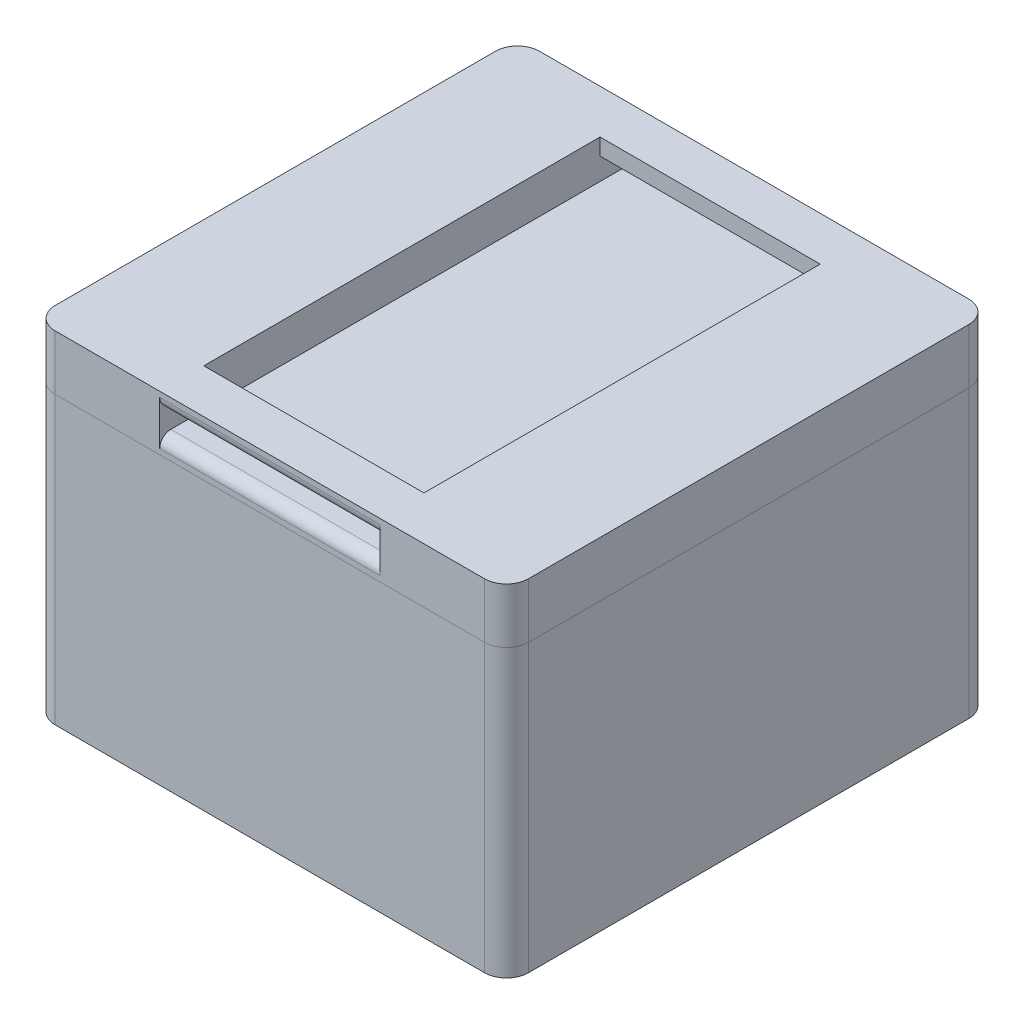
SolidWorks part; units mm, degrees
other "Boks"
other "Lokk"
ref_plane "Front Plane" through (0, 0, 0) normal (0, 0, 1) x (1, 0, 0)
ref_plane "Top Plane" through (0, 0, 0) normal (0, 1, 0) x (1, 0, 0)
ref_plane "Right Plane" through (0, 0, 0) normal (1, 0, 0) x (0, 0, -1)
sketch "Sketch1" plane through (0, 0, 0) normal (0, 1, 0) x (1, 0, 0)
  line L1 (19.5, -22) -> (-19.5, -22)
  line L2 (21.5, -20) -> (21.5, 20)
  line L3 (19.5, 22) -> (-19.5, 22)
  line L4 (-21.5, -20) -> (-21.5, 20)
  line L5 (21.5, -22) -> (-21.5, 22) construction
  line L6 (21.5, 22) -> (-21.5, -22) construction
  arc A0 (19.5, 22) -> (21.5, 20) centre (19.5, 20) cw
  arc A1 (21.5, -20) -> (19.5, -22) centre (19.5, -20) cw
  arc A2 (-19.5, -22) -> (-21.5, -20) centre (-19.5, -20) cw
  arc A3 (-21.5, 20) -> (-19.5, 22) centre (-19.5, 20) cw
  point P0 (0, 0)
  dimension "D3" = 2
  dimension "D1" = 43
  dimension "D2" = 44
extrude "Boss-Extrude1" add sketch "Sketch1" along normal blind 2
sketch "Sketch2" plane through (0, 2, 0) normal (0, 1, 0) x (1, 0, 0)
  line L1 (-17.8, -4.8) -> (1, -4.8)
  line L2 (-17.8, -4.8) -> (-17.8, -19)
  line L3 (-17.8, -19) -> (1, -19)
  line L4 (1, -4.8) -> (1, -19)
  line L5 (2, -3.2) -> (17.1, -3.2)
  line L6 (2, -3.2) -> (2, -19)
  line L7 (2, -19) -> (17.1, -19)
  line L8 (17.1, -3.2) -> (17.1, -19)
  line L10 (-19.5, -22) -> (19.5, -22) construction
  line L14 (-21.5, 20) -> (-21.5, -20) construction
  point P16 (-8.4, -19)
  dimension "D1" = 18.8
  dimension "D2" = 14.2
  dimension "D3" = 15.1
  dimension "D4" = 15.8
  dimension "D5" = 1
  dimension "D6" = 3
  dimension "D7" = 3.7
  dimension "D8" = 3
extrude "Cut-Extrude1" cut sketch "Sketch2" against normal blind 1.4
sketch "Sketch3" plane through (0, 0.6, 0) normal (0, 1, 0) x (1, 0, 0)
  line L16 (-8.4, -4.8) -> (-8.4, -9.3385) construction
  line L17 (-17.8, -4.8) -> (-15.8, -4.8) construction
  line L18 (-17.8, -4.8) -> (-17.8, -6.8) construction
  line L19 (-17.8, -6.8) -> (-15.8, -6.8)
  line L20 (-15.8, -4.8) -> (-15.8, -6.8)
  line L21 (1, -4.8) -> (-17.8, -4.8) construction
  line L22 (-1, -4.8) -> (-1, -6.8)
  line L23 (1, -6.8) -> (-1, -6.8)
  line L24 (1, -4.8) -> (1, -6.8) construction
  line L25 (1, -4.8) -> (-1, -4.8) construction
  line L26 (1, -19) -> (1, -4.8) construction
  line L27 (-17.8, -19) -> (1, -19) construction
  line L28 (-17.8, -19) -> (-17.8, -18.5) construction
  line L29 (-17.8, -18.5) -> (1, -18.5)
  line L30 (1, -19) -> (1, -18.5) construction
  line L31 (-17.8, -6.8) -> (-17.8, -18.5)
  line L32 (-15.8, -4.8) -> (-1, -4.8)
  line L33 (1, -6.8) -> (1, -18.5)
  line L34 (2, -3.2) -> (2, -19) construction
  line L35 (2, -18.5) -> (17.1, -18.5)
  line L36 (2, -18.5) -> (2, -8.2)
  line L37 (2, -8.2) -> (17.1, -8.2)
  line L38 (17.1, -18.5) -> (17.1, -8.2)
  line L39 (17.1, -19) -> (17.1, -3.2) construction
  line L40 (2, -19) -> (17.1, -19) construction
  line L41 (17.1, -3.2) -> (2, -3.2) construction
  dimension "D1" = 2
  dimension "D2" = 2
  dimension "D3" = 0.5
  dimension "D4" = 0.5
  dimension "D5" = 5
extrude "Cut-Extrude2" cut sketch "Sketch3" against normal through all
sketch "Sketch13" plane through (0, 2, 0) normal (0, 1, 0) x (1, 0, 0)
  line L8 (19.5, 20.5) -> (-19.5, 20.5)
  line L9 (-20, 20) -> (-20, -20)
  line L10 (-19.5, -20.5) -> (19.5, -20.5)
  line L11 (20, -20) -> (20, 20)
  line L12 (19, 20.5) -> (-19, 20.5)
  line L13 (-20, 19.5) -> (-20, -19.5)
  line L14 (-19, -20.5) -> (19, -20.5)
  line L15 (20, -19.5) -> (20, 19.5)
  arc A0 (-20, 19.5) -> (-19, 20.5) centre (-19, 19.5) cw
  arc A1 (-19, -20.5) -> (-20, -19.5) centre (-19, -19.5) cw
  arc A2 (19, -20.5) -> (20, -19.5) centre (19, -19.5) ccw
  arc A3 (20, 19.5) -> (19, 20.5) centre (19, 19.5) ccw
  arc A11 (20, 20) -> (19.5, 20.5) centre (19.5, 20) ccw
  arc A12 (20, 20) -> (19.5, 20.5) centre (19.5, 20) ccw
  arc A13 (-19.5, 20.5) -> (-20, 20) centre (-19.5, 20) ccw
  arc A14 (-19.5, 20.5) -> (-20, 20) centre (-19.5, 20) ccw
  arc A15 (-20, -20) -> (-19.5, -20.5) centre (-19.5, -20) ccw
  arc A16 (-20, -20) -> (-19.5, -20.5) centre (-19.5, -20) ccw
  arc A17 (19.5, -20.5) -> (20, -20) centre (19.5, -20) ccw
  arc A18 (19.5, -20.5) -> (20, -20) centre (19.5, -20) ccw
  arc M17 (21.5, 20) -> (19.5, 22) centre (19.5, 20) ccw
  line M18 (19.5, 22) -> (-19.5, 22)
  arc M19 (-19.5, 22) -> (-21.5, 20) centre (-19.5, 20) ccw
  line M20 (-21.5, 20) -> (-21.5, -20)
  arc M21 (-21.5, -20) -> (-19.5, -22) centre (-19.5, -20) ccw
  line M22 (-19.5, -22) -> (19.5, -22)
  arc M23 (19.5, -22) -> (21.5, -20) centre (19.5, -20) ccw
  line M24 (21.5, -20) -> (21.5, 20)
  dimension "D2" = 1
  dimension "D1" = 1.5
extrude "Boss-Extrude3" add sketch "Sketch13" along normal blind 24 contours A18 L14 A16 L13 A14 L12 A12 L15 M24 M17 M18 M19 M20 M21 M22 M23
sketch "Sketch16" plane through (-20, 0, 0) normal (1, 0, 0) x (0, 0, -1)
  line L0 (19.5, 2) -> (-19.5, 2) construction
  line L1 (19, 12) -> (13.5152, 21.5) construction
  line L2 (13.5152, 21.5) -> (2.5455, 21.5) construction
  line L3 (2.5455, 21.5) -> (-2.9393, 12) construction
  line L4 (-2.9393, 12) -> (2.5455, 2.5) construction
  line L5 (2.5455, 2.5) -> (13.5152, 2.5) construction
  line L6 (13.5152, 2.5) -> (19, 12) construction
  line L7 (19.5, 26) -> (19.5, 2) construction
  circle A0 centre (8.0303, 12) radius 5.65
  circle A1 centre (8.0303, 12) radius 9.5 construction
  point P2 (17.4001, 15.4975)
  dimension "D1" = 11.3
  dimension "D2" = 19
  dimension "D3" = 0.5
  dimension "D4" = 0.5
extrude "Cut-Extrude6" cut sketch "Sketch16" against normal blind 19
sketch "Sketch17" plane through (0, 26, 0) normal (0, 1, 0) x (1, 0, 0)
  line L8 (21.5, -20) -> (21.5, 20)
  line L9 (19.5, 22) -> (-19.5, 22)
  line L10 (-21.5, 20) -> (-21.5, -20)
  line L11 (-19.5, -22) -> (19.5, -22)
  line L12 (21.5, -20) -> (21.5, 20)
  line L13 (19.5, 22) -> (-19.5, 22)
  line L14 (-21.5, 20) -> (-21.5, -20)
  line L15 (-19.5, -22) -> (19.5, -22)
  arc A8 (21.5, 20) -> (19.5, 22) centre (19.5, 20) ccw
  arc A9 (-19.5, 22) -> (-21.5, 20) centre (-19.5, 20) ccw
  arc A10 (-21.5, -20) -> (-19.5, -22) centre (-19.5, -20) ccw
  arc A11 (19.5, -22) -> (21.5, -20) centre (19.5, -20) ccw
  arc A12 (21.5, 20) -> (19.5, 22) centre (19.5, 20) ccw
  arc A13 (-19.5, 22) -> (-21.5, 20) centre (-19.5, 20) ccw
  arc A14 (-21.5, -20) -> (-19.5, -22) centre (-19.5, -20) ccw
  arc A15 (19.5, -22) -> (21.5, -20) centre (19.5, -20) ccw
  dimension "D1" = 0
extrude "Boss-Extrude4" add sketch "Sketch17" along normal blind 5 separate body
sketch "Sketch19" plane through (0, 26, 0) normal (0, -1, 0) x (1, 0, 0)
  line L0 (20, 19.5) -> (20, -19.5) construction
  line L1 (19, -20.5) -> (-19, -20.5) construction
  line L2 (-20, -19.5) -> (-20, 19.5) construction
  line L3 (-19, 20.5) -> (19, 20.5) construction
  line L4 (20, 19.5) -> (20, -19.5)
  line L5 (19, -20.5) -> (-19, -20.5)
  line L6 (-20, -19.5) -> (-20, 19.5)
  line L7 (-19, 20.5) -> (19, 20.5)
  line L8 (18, 18.5) -> (18, -18.5)
  line L9 (18, -18.5) -> (-18, -18.5)
  line L10 (-18, -18.5) -> (-18, 18.5)
  line L11 (-18, 18.5) -> (18, 18.5)
  arc A0 (20, 19.5) -> (19, 20.5) centre (19, 19.5) ccw construction
  arc A1 (19, -20.5) -> (20, -19.5) centre (19, -19.5) ccw construction
  arc A2 (-20, -19.5) -> (-19, -20.5) centre (-19, -19.5) ccw construction
  arc A3 (-19, 20.5) -> (-20, 19.5) centre (-19, 19.5) ccw construction
  arc A4 (20, 19.5) -> (19, 20.5) centre (19, 19.5) ccw
  arc A5 (19, -20.5) -> (20, -19.5) centre (19, -19.5) ccw
  arc A6 (-20, -19.5) -> (-19, -20.5) centre (-19, -19.5) ccw
  arc A7 (-19, 20.5) -> (-20, 19.5) centre (-19, 19.5) ccw
  arc A8 (18, -18.5) -> (18, -18.5) centre (18, -18.5) ccw
  arc A9 (-18, -18.5) -> (-18, -18.5) centre (-18, -18.5) ccw
  arc A10 (-18, 18.5) -> (-18, 18.5) centre (-18, 18.5) ccw
  arc A11 (18, 18.5) -> (18, 18.5) centre (18, 18.5) ccw
  dimension "D1" = 2
extrude "Boss-Extrude5" add sketch "Sketch19" along normal blind 3
sketch "Sketch20" plane through (0, 0, 22) normal (0, 0, 1) x (1, 0, 0)
  line L0 (0, 29.5) -> (0, 31) construction
  line L1 (-10, 29.5) -> (10, 29.5)
  line L2 (-10, 29.5) -> (-10, 27.5)
  line L3 (-10, 27.5) -> (10, 27.5)
  line L4 (10, 29.5) -> (10, 27.5)
  line L5 (-19.5, 31) -> (19.5, 31) construction
  line L6 (-10, 28.5) -> (-19.5, 28.5) construction
  line L7 (-19.5, 31) -> (-19.5, 26) construction
  dimension "D1" = 2
  dimension "D2" = 20
extrude "Cut-Extrude7" cut sketch "Sketch20" against normal up to body
fillet "Fillet1" radius 1 4 edges at (0, 29.5, 22) (0, 27.5, 22) (0, 29.5, -22) (0, 27.5, -22)
sketch "Sketch21" plane through (0, 29.5, 0) normal (0, -1, 0) x (1, 0, 0)
  line L0 (-10, -21) -> (-10, 21) construction
  line L1 (-10, 18) -> (10, 18)
  line L2 (-10, 18) -> (-10, -18)
  line L3 (-10, -18) -> (10, -18)
  line L4 (10, 18) -> (10, -18)
  line L5 (10, -21) -> (10, 21) construction
  line L6 (-10, 22) -> (10, 22) construction
  line L7 (10, -22) -> (-10, -22) construction
  dimension "D1" = 4
  dimension "D2" = 4
extrude "Cut-Extrude8" cut sketch "Sketch21" against normal up to surface (1.5 mm away) up to face at (0, 31, 0)
